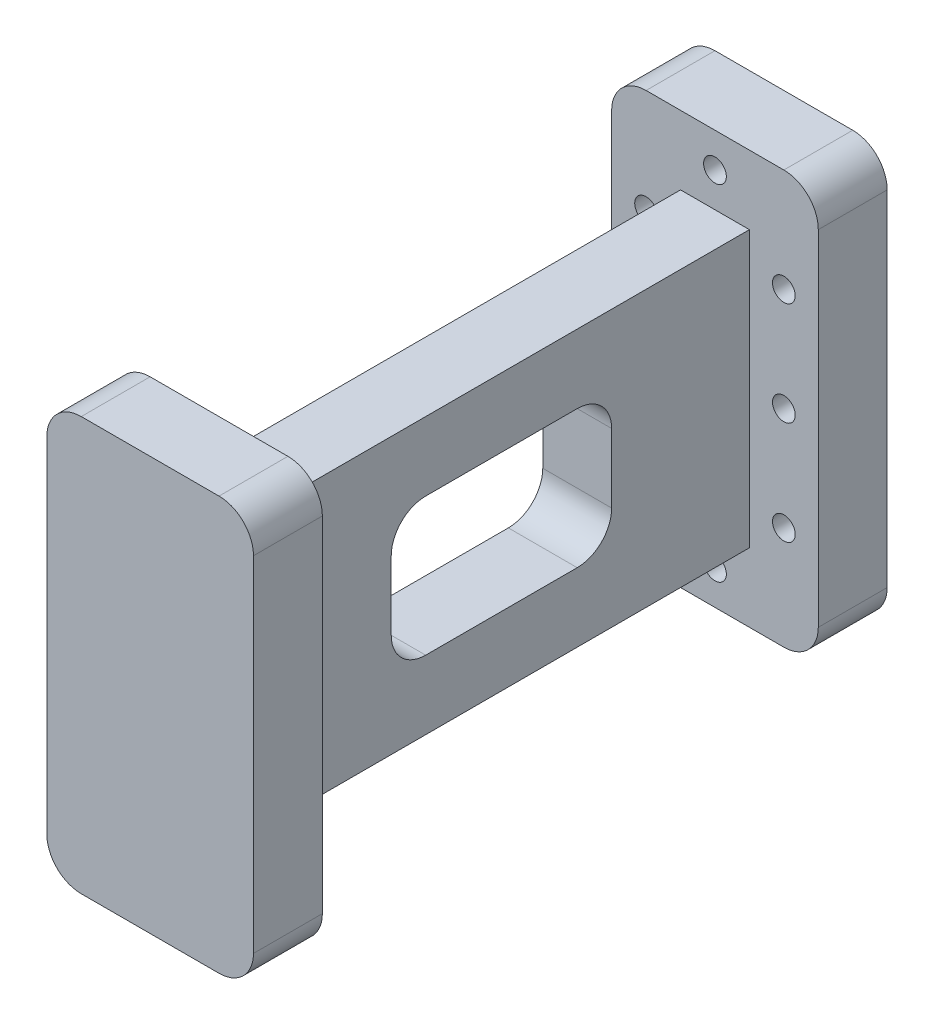
SolidWorks part; units mm, degrees
ref_plane "Front Plane" through (0, 0, 0) normal (0, 0, 1) x (1, 0, 0)
ref_plane "Top Plane" through (0, 0, 0) normal (0, 1, 0) x (1, 0, 0)
ref_plane "Right Plane" through (0, 0, 0) normal (1, 0, 0) x (0, 0, -1)
sketch "Sketch1" plane through (0, 0, 0) normal (0, 0, 1) x (1, 0, 0)
  line L1 (-10, -30) -> (10, -30)
  line L2 (-15, -25) -> (-15, 25)
  line L3 (-10, 30) -> (10, 30)
  line L4 (15, -25) -> (15, 25)
  line L5 (-15, -30) -> (15, 30) construction
  line L6 (-15, 30) -> (15, -30) construction
  arc A0 (-15, 25) -> (-10, 30) centre (-10, 25) cw
  arc A1 (10, 30) -> (15, 25) centre (10, 25) cw
  arc A2 (10, -30) -> (15, -25) centre (10, -25) ccw
  arc A3 (-10, -30) -> (-15, -25) centre (-10, -25) cw
  point P0 (0, 0)
  dimension "D3" = 5
  dimension "D1" = 60
  dimension "D2" = 30
extrude "Boss-Extrude1" add sketch "Sketch1" along normal blind 92
sketch "Sketch2" plane through (15, 0, 0) normal (1, 0, 0) x (0, 0, -1)
  line L0 (-92, 30) -> (-92, 0)
  line L1 (-10, 0) -> (-10, 30)
  line L2 (-92, 30) -> (0, 30) construction
  line L3 (-92, -25) -> (-92, 25) construction
  line L5 (-82, 30) -> (-82, -30)
  line L6 (-92, 30) -> (-82, 30)
  line L7 (-10, 30) -> (-10, -30)
  line L8 (-92, -30) -> (0, -30) construction
extrude "Cut-Extrude1" cut sketch "Sketch2" against normal blind 10 and the other way through all
sketch "Sketch3" plane through (-15, 0, 0) normal (-1, 0, 0) x (0, 0, 1)
  line L0 (0, 30) -> (10, 30)
  line L1 (92, 30) -> (0, 30) construction
  line L2 (10, 30) -> (10, -30)
  line L3 (92, -30) -> (0, -30) construction
  line L4 (92, 30) -> (82, 30)
  line L5 (82, 30) -> (82, -30)
  line L6 (82, 30) -> (10, 30)
  line L7 (10, -30) -> (82, -30)
extrude "Cut-Extrude2" cut sketch "Sketch3" against normal blind 10
sketch "Sketch4" plane through (-5, 0, 0) normal (-1, 0, 0) x (0, 0, 1)
  line L0 (82, 30) -> (82, 20)
  line L1 (82, 25) -> (82, -25) construction
  line L2 (82, 20) -> (10, 20)
  line L3 (10, 25) -> (10, -25) construction
  line L4 (10, 20) -> (10, 30)
  line L5 (10, 30) -> (82, 30)
extrude "Cut-Extrude3" cut sketch "Sketch4" against normal blind 10
sketch "Sketch5" plane through (-5, 0, 0) normal (-1, 0, 0) x (0, 0, 1)
  line L0 (10, -30) -> (10, -20)
  line L1 (10, 20) -> (10, -25) construction
  line L2 (10, -20) -> (82, -20)
  line L3 (82, 20) -> (82, -25) construction
  line L4 (82, -20) -> (82, -30)
  line L5 (82, -30) -> (10, -30)
extrude "Cut-Extrude4" cut sketch "Sketch5" against normal blind 10
sketch "Sketch6" plane through (0, 0, 92) normal (0, 0, 1) x (1, 0, 0)
  line L0 (9.9, 20.4) -> (9.9, -20.4)
  line L1 (9.9, -20.4) -> (-9.9, -20.4)
  line L7 (0, -20.4) -> (9.9, -20.4)
  line L9 (9.9, -20.4) -> (-9.9, -20.4)
  line L10 (-15, 25) -> (-15, -25) construction
  line L11 (-15, -20.4) -> (-15, 20.4)
  line L12 (-9.9, 20.4) -> (9.9, 20.4)
  line L14 (-9.9, -20.4) -> (-9.9, 20.4)
sketch "Sketch7" plane through (0, 0, 10) normal (0, 0, 1) x (1, 0, 0)
  line L0 (5, 0) -> (15, 0)
  line L1 (5, 20) -> (5, -20) construction
  line L2 (15, 25) -> (15, -25) construction
  line L3 (15, 0) -> (10, 0)
  line L4 (10, 0) -> (10, 30)
  line L5 (5, 30) -> (-5, 30) construction
  line L6 (10, 30) -> (10, -30)
  line L7 (5, -30) -> (-5, -30) construction
  line L8 (10, -30) -> (10, 0)
  line L9 (10, 0) -> (10, 15)
  line L10 (10, 0) -> (10, -30)
  circle A0 centre (10, 15) radius 1.6218
  circle A1 centre (10, 0) radius 1.7997
  circle A2 centre (10, -15) radius 1.0519
hole_wizard "M4x0.7 Tapped Hole1" positions "Sketch8" profile "Sketch9" tap size "M4x0.7" standard "ANSI Metric"
sketch "Sketch8" plane through (0, 0, 10) normal (0, 0, 1) x (1, 0, 0)
  point P0 (10, -15)
sketch "Sketch9" plane through (10, -15, 10) normal (1, 0, 0) x (0, -1, 0)
  line L0 (0, 0) -> (0, 10)
  line L1 (0, 10) -> (1.65, 10)
  line L2 (1.65, 10) -> (1.65, 0)
  line L5 (1.65, 0) -> (0, 0)
  line L11 (0, -6.35) -> (0, 107.95) construction
  dimension "Thru Tap Drill Dia." = 3.3
  dimension "Thru Tap Drill Depth" = 10
cosmetic thread "Hole Thread1" parameters "D2"=4
hole_wizard "M4x0.7 Tapped Hole2" positions "Sketch10" profile "Sketch11" tap size "M4x0.7" standard "ANSI Metric"
sketch "Sketch10" plane through (0, 0, 10) normal (0, 0, 1) x (1, 0, 0)
  point P0 (10, 0)
sketch "Sketch11" plane through (10, 0, 10) normal (1, 0, 0) x (0, -1, 0)
  line L0 (0, 0) -> (0, 10)
  line L1 (0, 10) -> (1.65, 10)
  line L2 (1.65, 10) -> (1.65, 0)
  line L5 (1.65, 0) -> (0, 0)
  line L11 (0, -6.35) -> (0, 107.95) construction
  dimension "Thru Tap Drill Dia." = 3.3
  dimension "Thru Tap Drill Depth" = 10
cosmetic thread "Hole Thread2" parameters "D2"=4
hole_wizard "M4x0.7 Tapped Hole3" positions "Sketch12" profile "Sketch13" tap size "M4x0.7" standard "ANSI Metric"
sketch "Sketch12" plane through (0, 0, 10) normal (0, 0, 1) x (1, 0, 0)
  point P0 (10, 15)
sketch "Sketch13" plane through (10, 15, 10) normal (1, 0, 0) x (0, -1, 0)
  line L0 (0, 0) -> (0, 10)
  line L1 (0, 10) -> (1.65, 10)
  line L2 (1.65, 10) -> (1.65, 0)
  line L5 (1.65, 0) -> (0, 0)
  line L11 (0, -6.35) -> (0, 107.95) construction
  dimension "Thru Tap Drill Dia." = 3.3
  dimension "Thru Tap Drill Depth" = 10
cosmetic thread "Hole Thread3" parameters "D2"=4
sketch "Sketch14" plane through (0, 0, 10) normal (0, 0, 1) x (1, 0, 0)
  line L4 (-10, 0) -> (-10, -30)
  line L5 (5, -30) -> (-5, -30) construction
  line L6 (-10, -30) -> (-10, 0)
  line L8 (-10, 0) -> (-10, 30)
  line L9 (-10, 0) -> (-5, 0)
  line L10 (-5, 20) -> (-5, -20) construction
  line L11 (5, 30) -> (-5, 30) construction
  line L12 (-10, 30) -> (-10, 15)
  line L13 (-10, 0) -> (-10, -15)
  circle A0 centre (-10, 15) radius 0.5411
  circle A1 centre (-10, 0) radius 0.8655
hole_wizard "M4x0.7 Tapped Hole4" positions "Sketch15" profile "Sketch16" tap size "M4x0.7" standard "ANSI Metric"
sketch "Sketch15" plane through (0, 0, 10) normal (0, 0, 1) x (1, 0, 0)
  point P0 (-10, -15)
sketch "Sketch16" plane through (-10, -15, 10) normal (1, 0, 0) x (0, -1, 0)
  line L0 (0, 0) -> (0, 10)
  line L1 (0, 10) -> (1.65, 10)
  line L2 (1.65, 10) -> (1.65, 0)
  line L5 (1.65, 0) -> (0, 0)
  line L11 (0, -6.35) -> (0, 107.95) construction
  dimension "Thru Tap Drill Dia." = 3.3
  dimension "Thru Tap Drill Depth" = 10
cosmetic thread "Hole Thread4" parameters "D2"=4
hole_wizard "M4x0.7 Tapped Hole5" positions "Sketch17" profile "Sketch18" tap size "M4x0.7" standard "ANSI Metric"
sketch "Sketch17" plane through (0, 0, 10) normal (0, 0, 1) x (1, 0, 0)
  point P0 (-10, 0)
sketch "Sketch18" plane through (-10, 0, 10) normal (1, 0, 0) x (0, -1, 0)
  line L0 (0, 0) -> (0, 10)
  line L1 (0, 10) -> (1.65, 10)
  line L2 (1.65, 10) -> (1.65, 0)
  line L5 (1.65, 0) -> (0, 0)
  line L11 (0, -6.35) -> (0, 107.95) construction
  dimension "Thru Tap Drill Dia." = 3.3
  dimension "Thru Tap Drill Depth" = 10
cosmetic thread "Hole Thread5" parameters "D2"=4
hole_wizard "M4x0.7 Tapped Hole6" positions "Sketch19" profile "Sketch20" tap size "M4x0.7" standard "ANSI Metric"
sketch "Sketch19" plane through (0, 0, 10) normal (0, 0, 1) x (1, 0, 0)
  point P0 (-10, 15)
sketch "Sketch20" plane through (-10, 15, 10) normal (1, 0, 0) x (0, -1, 0)
  line L0 (0, 0) -> (0, 10)
  line L1 (0, 10) -> (1.65, 10)
  line L2 (1.65, 10) -> (1.65, 0)
  line L5 (1.65, 0) -> (0, 0)
  line L11 (0, -6.35) -> (0, 107.95) construction
  dimension "Thru Tap Drill Dia." = 3.3
  dimension "Thru Tap Drill Depth" = 10
cosmetic thread "Hole Thread6" parameters "D2"=4
sketch "Sketch21" plane through (0, 0, 10) normal (0, 0, 1) x (1, 0, 0)
  line L0 (-5, 20) -> (-5, 25)
  line L2 (15, 25) -> (-15, 25)
  line L3 (15, 25) -> (15, -25) construction
  line L5 (-15, 25) -> (-15, -25) construction
  circle A0 centre (0, 25) radius 0.4899
hole_wizard "M4x0.7 Tapped Hole7" positions "Sketch22" profile "Sketch23" tap size "M4x0.7" standard "ANSI Metric"
sketch "Sketch22" plane through (0, 0, 10) normal (0, 0, 1) x (1, 0, 0)
  point P0 (0, 25)
sketch "Sketch23" plane through (0, 25, 10) normal (1, 0, 0) x (0, -1, 0)
  line L0 (0, 0) -> (0, 10)
  line L1 (0, 10) -> (1.65, 10)
  line L2 (1.65, 10) -> (1.65, 0)
  line L5 (1.65, 0) -> (0, 0)
  line L11 (0, -6.35) -> (0, 107.95) construction
  dimension "Thru Tap Drill Dia." = 3.3
  dimension "Thru Tap Drill Depth" = 10
cosmetic thread "Hole Thread7" parameters "D2"=4
sketch "Sketch24" plane through (0, 0, 10) normal (0, 0, 1) x (1, 0, 0)
  line L0 (-5, -20) -> (-5, -30)
  line L1 (5, -30) -> (-5, -30) construction
  line L2 (-5, -30) -> (-5, -25)
  line L3 (-5, -25) -> (15, -25)
  line L4 (15, 25) -> (15, -25) construction
  line L5 (15, -25) -> (-15, -25)
  line L6 (-15, 25) -> (-15, -25) construction
  circle A0 centre (0, -25) radius 1.5326
hole_wizard "M4x0.7 Tapped Hole8" positions "Sketch25" profile "Sketch26" tap size "M4x0.7" standard "ANSI Metric"
sketch "Sketch25" plane through (0, 0, 10) normal (0, 0, 1) x (1, 0, 0)
  point P0 (0, -25)
sketch "Sketch26" plane through (0, -25, 10) normal (1, 0, 0) x (0, -1, 0)
  line L0 (0, 0) -> (0, 10)
  line L1 (0, 10) -> (1.65, 10)
  line L2 (1.65, 10) -> (1.65, 0)
  line L5 (1.65, 0) -> (0, 0)
  line L11 (0, -6.35) -> (0, 107.95) construction
  dimension "Thru Tap Drill Dia." = 3.3
  dimension "Thru Tap Drill Depth" = 10
cosmetic thread "Hole Thread8" parameters "D2"=4
sketch "Sketch27" plane through (-5, 0, 0) normal (-1, 0, 0) x (0, 0, 1)
  line L0 (82, 20) -> (82, -20)
  line L1 (82, -20) -> (82, 0)
  line L5 (62, 0) -> (62, 5)
  line L6 (57, 10) -> (35, 10)
  line L7 (30, 5) -> (30, 0)
  line L8 (30, 0) -> (30, -5)
  line L9 (35, -10) -> (57, -10)
  line L10 (62, -5) -> (62, 0)
  arc A0 (57, -10) -> (62, -5) centre (57, -5) ccw
  arc A1 (62, 5) -> (57, 10) centre (57, 5) ccw
  arc A2 (30, -5) -> (35, -10) centre (35, -5) ccw
  arc A3 (35, 10) -> (30, 5) centre (35, 5) ccw
  dimension "D1" = 5
extrude "Cut-Extrude5" cut sketch "Sketch27" against normal blind 10 contours L9 L10 L5 L6 L7 L8
sketch "Sketch28" plane through (0, 0, 10) normal (0, 0, 1) x (1, 0, 0)
  line L0 (10, 30) -> (-10, 30)
  line L1 (-15, 25) -> (-15, -25)
  line L2 (-10, -30) -> (10, -30)
  line L3 (15, -25) -> (15, 25)
  arc A0 (10, -30) -> (15, -25) centre (10, -25) ccw
  arc A1 (-15, -25) -> (-10, -30) centre (-10, -25) ccw
  arc A2 (-10, 30) -> (-15, 25) centre (-10, 25) ccw
  arc A3 (10, 30) -> (15, 25) centre (10, 25) cw
  point P10 (15, -30)
  point P13 (-15, -30)
  point P16 (-15, 30)
  point P19 (15, 30)
  dimension "D1" = 5
sketch "Sketch29" plane through (-15, 0, 0) normal (-1, 0, 0) x (0, 0, 1)
  line L0 (82, 25) -> (82, 39.4355)
  line L1 (82, 39.4355) -> (10, 39.4355)
  line L2 (10, 39.4355) -> (10, -37.1308)
  line L3 (10, -37.1308) -> (82, -37.1308)
  line L4 (82, -37.1308) -> (82, 39.4355)
  line M1 (82, 25) -> (82, -25)
extrude "Cut-Extrude8" cut sketch "Sketch29" against normal blind 10 contours L3 L4 L0 L1 L2 M1
sketch "Sketch30" plane through (15, 0, 0) normal (1, 0, 0) x (0, 0, -1)
  line L0 (-82, -25) -> (-82, -44.1879)
  line L2 (-10, -25) -> (-10, 35.9213)
  line L3 (-10, 35.9213) -> (-82, 35.9213)
  line L4 (-82, 35.9213) -> (-82, -44.1879)
  line L5 (-10, -25) -> (-10, -44.1879)
  line L6 (-10, -44.1879) -> (-82, -44.1879)
  line M1 (-82, -25) -> (-82, 25)
extrude "Cut-Extrude9" cut sketch "Sketch30" against normal blind 10 contours L6 L5 L2 L3 L4 L0 M1
